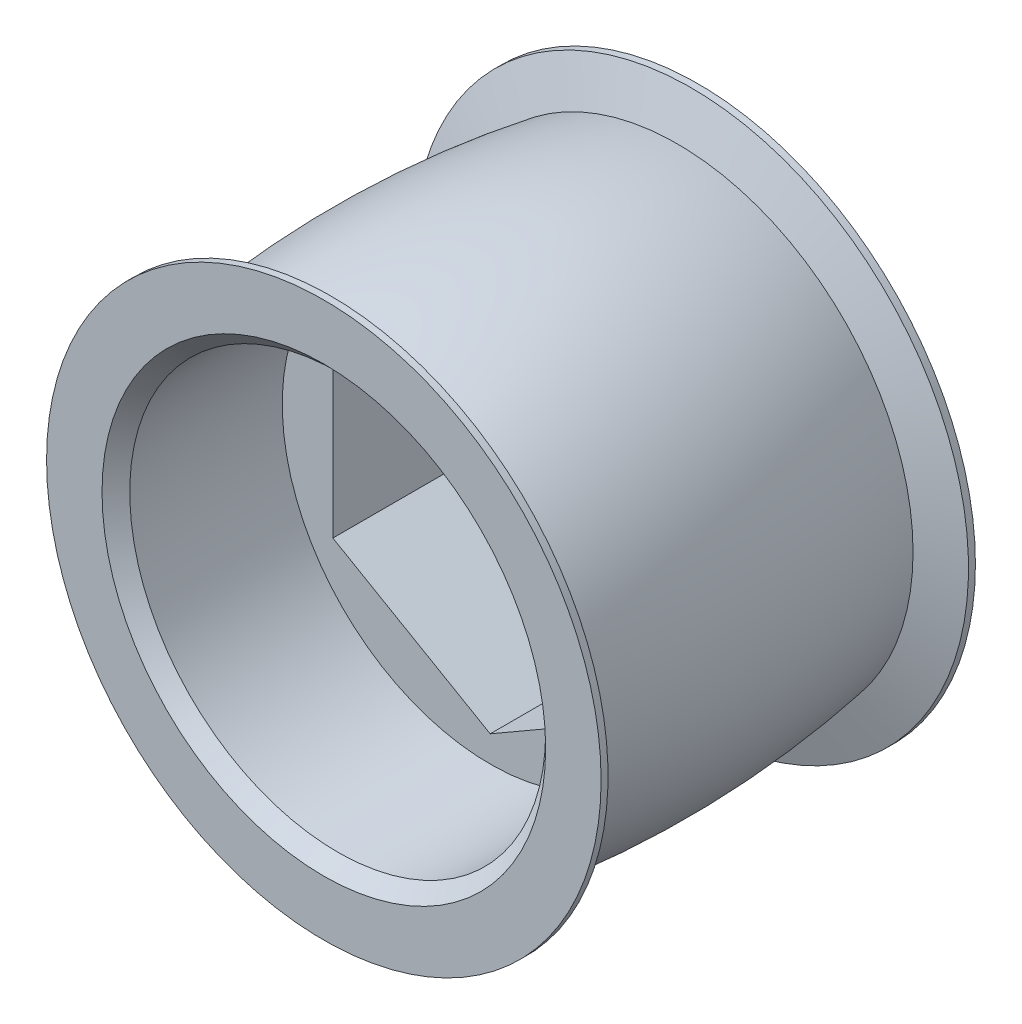
SolidWorks part; units mm, degrees
ref_plane "Plan de face" through (0, 0, 0) normal (0, 0, 1) x (1, 0, 0)
ref_plane "Plan de dessus" through (0, 0, 0) normal (0, 1, 0) x (1, 0, 0)
ref_plane "Plan de droite" through (0, 0, 0) normal (1, 0, 0) x (0, 0, -1)
sketch "Esquisse1" plane through (0, 0, 0) normal (0, 0, 1) x (1, 0, 0)
  circle A0 centre (0, 0) radius 3.25
  circle A1 centre (0, 0) radius 20
  dimension "D1" = 40
  dimension "D2" = 6.5
extrude "Boss.-Extru.1" add sketch "Esquisse1" along normal blind 15
sketch "Esquisse2" plane through (0, 0, 15) normal (0, 0, 1) x (1, 0, 0)
  circle A0 centre (0, 0) radius 20
  circle A1 centre (0, 0) radius 15
  circle A2 centre (0, 0) radius 20 construction
  dimension "D1" = 30
extrude "Boss.-Extru.2" add sketch "Esquisse2" along normal blind 12
sketch "Esquisse9" plane through (0, 0, 15) normal (0, 0, 1) x (1, 0, 0)
  line L0 (0, 0) -> (0, 26.2117) construction
  line L1 (11.35, -6.5529) -> (11.35, 6.5529)
  line L2 (11.35, 6.5529) -> (0, 13.1059)
  line L3 (0, 13.1059) -> (-11.35, 6.5529)
  line L4 (-11.35, 6.5529) -> (-11.35, -6.5529)
  line L5 (-11.35, -6.5529) -> (0, -13.1059)
  line L6 (0, -13.1059) -> (11.35, -6.5529)
  circle A0 centre (0, 0) radius 11.35 construction
  dimension "D1" = 22.7
extrude "Enlèv. mat.-Extru.9" cut sketch "Esquisse9" against normal offset from surface (8 mm away) 7 up to face at (20, 0, 0)
chamfer "Chanfrein1" distance 1 angle 45 1 edges at (15, 0, 27)
sketch "Esquisse10" plane through (0, 0, 0) normal (1, 0, 0) x (0, 0, -1)
  line L0 (-26.5, 20) -> (-0.5, 20)
  line L1 (0, 20) -> (-27, 20) construction
  line L2 (-0.5, 20) -> (-1.5, 17)
  line L3 (-1.5, 17) -> (-25.5, 17) construction
  line L4 (-25.5, 17) -> (-26.5, 20)
  line L5 (-19.6787, 18) -> (-7.7815, 18) construction
  line L6 (0, 0) -> (-50.6564, 0) construction
  arc A0 (-25.5, 17) -> (-1.5, 17) centre (-13.5, -54.5) cw
  dimension "D6" = 1
  dimension "D1" = 3
  dimension "D2" = 0.5
  dimension "D3" = 0.5
  dimension "D4" = 1
  dimension "D5" = 1
revolve "Enlèvement de matière-Révolution1" cut sketch "Esquisse10" angle 360 about L6
sketch "Esquisse11" plane through (0, 0, 0) normal (0, 0, -1) x (-1, 0, 0)
  line L0 (0, 0) -> (17.3205, 10) construction
  line L1 (0, 0) -> (-17.3205, 10) construction
  line L2 (0, 0) -> (0, -20) construction
  circle A0 centre (0, 0) radius 20 construction
  circle A1 centre (-6.9282, 4) radius 1.25
  circle A2 centre (6.9282, 4) radius 1.25
  circle A3 centre (0, -8) radius 1.25
  circle A4 centre (0, 0) radius 8 construction
  dimension "D3" = 2.5
  dimension "D4" = 16
  dimension "D1" = 120
  dimension "D2" = 120
extrude "Enlèv. mat.-Extru.10" cut sketch "Esquisse11" against normal through all
sketch "Esquisse12" plane through (0, 0, 0) normal (0, 0, -1) x (-1, 0, 0)
  circle A0 centre (-6.9282, 4) radius 4.25
  circle A1 centre (6.9282, 4) radius 4.25
  circle A2 centre (0, -8) radius 4.25
  dimension "D1" = 8.5
extrude "Enlèv. mat.-Extru.11" cut sketch "Esquisse12" against normal blind 4
